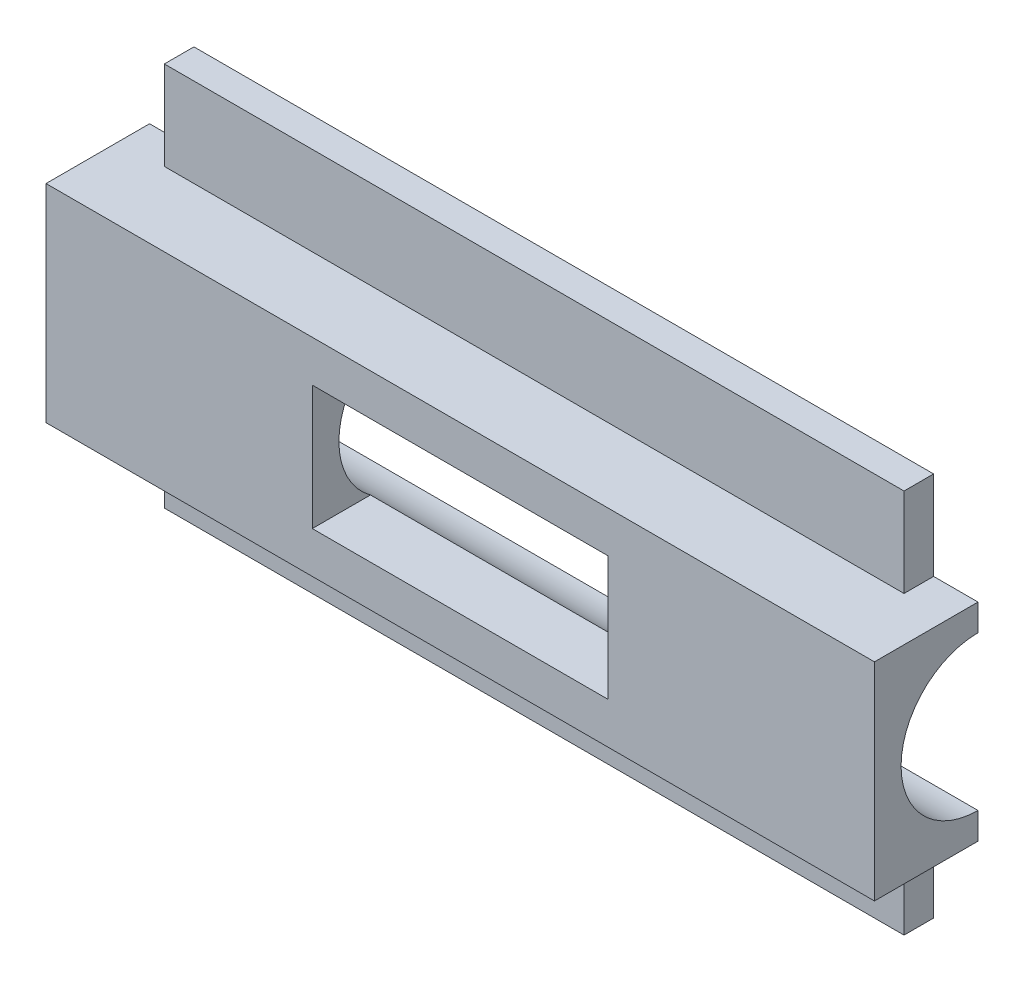
SolidWorks part; units mm, degrees
ref_plane "Alzado" through (0, 0, 0) normal (0, 0, 1) x (1, 0, 0)
ref_plane "Planta" through (0, 0, 0) normal (0, 1, 0) x (1, 0, 0)
ref_plane "Vista lateral" through (0, 0, 0) normal (1, 0, 0) x (0, 0, -1)
sketch "Croquis2" plane through (0, 0, 0) normal (0, 0, 1) x (1, 0, 0)
  line L2 (-70, 162.5) -> (70, 162.5)
  line L3 (-70, 162.5) -> (-70, 127.5)
  line L4 (-70, 127.5) -> (70, 127.5)
  line L5 (70, 162.5) -> (70, 127.5)
  dimension "D1" = 140
  dimension "D2" = 35
extrude "Saliente-Extruir1" add sketch "Croquis2" along normal blind 17.5
sketch "Croquis3" plane through (0, 127.5, 0) normal (0, -1, 0) x (1, 0, 0)
  line L0 (-70, 0) -> (70, 0) construction
  line L1 (-62.5, 0) -> (62.5, 0)
  line L2 (-62.5, 0) -> (-62.5, 5)
  line L3 (-62.5, 5) -> (62.5, 5)
  line L4 (62.5, 0) -> (62.5, 5)
  line L5 (0, -32.9433) -> (0, 44.2048) construction
  point P9 (0, 0)
  dimension "D1" = 5
  dimension "D2" = 125
extrude "Saliente-Extruir2" add sketch "Croquis3" along normal blind 15 and the other way blind 50
sketch "Croquis4" plane through (70, 0, 0) normal (1, 0, 0) x (0, 0, -1)
  circle A0 centre (0, 145) radius 13
  dimension "D1" = 26
extrude "Cortar-Extruir1" cut sketch "Croquis4" against normal up to surface (140 mm away) up to face at (-70, 145, 8.75)
sketch "Croquis5" plane through (0, 0, 17.5) normal (0, 0, 1) x (1, 0, 0)
  line L0 (0, 100.3416) -> (0, 197.4064) construction
  line L1 (70, 162.5) -> (-70, 162.5) construction
  line L2 (-70, 127.5) -> (70, 127.5) construction
  line L3 (25, 155.5) -> (-25, 155.5)
  line L4 (25, 155.5) -> (25, 134.5)
  line L5 (25, 134.5) -> (-25, 134.5)
  line L6 (-25, 155.5) -> (-25, 134.5)
  line L7 (25, 155.5) -> (-25, 134.5) construction
  line L8 (25, 134.5) -> (-25, 155.5) construction
  point P5 (-6.1316, 143.1573)
  point P13 (0, 0)
  dimension "D1" = 7
  dimension "D2" = 7
  dimension "D3" = 50
extrude "Cortar-Extruir2" cut sketch "Croquis5" against normal through all
